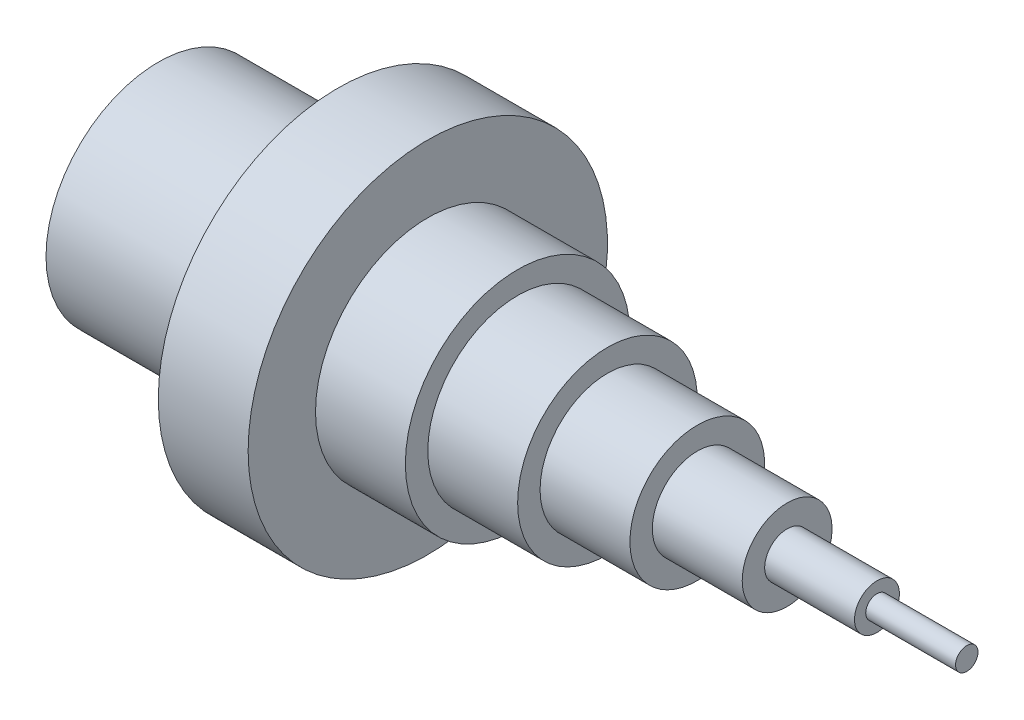
SolidWorks part; units mm, degrees
ref_plane "Alzado" through (0, 0, 0) normal (0, 0, 1) x (1, 0, 0)
ref_plane "Planta" through (0, 0, 0) normal (0, 1, 0) x (1, 0, 0)
ref_plane "Vista lateral" through (0, 0, 0) normal (1, 0, 0) x (0, 0, -1)
sketch "Croquis1" plane through (0, 0, 0) normal (0, 0, 1) x (1, 0, 0)
  line L0 (0, 0) -> (0, 25)
  line L1 (0, 25) -> (40, 25)
  line L2 (40, 25) -> (40, 40)
  line L3 (40, 40) -> (60, 40)
  line L4 (60, 40) -> (60, 25)
  line L5 (60, 25) -> (80, 25)
  line L6 (80, 25) -> (80, 20)
  line L7 (80, 20) -> (100, 20)
  line L8 (100, 20) -> (100, 15)
  line L9 (100, 15) -> (120, 15)
  line L10 (120, 15) -> (120, 10)
  line L11 (120, 10) -> (140, 10)
  line L12 (140, 10) -> (140, 5)
  line L13 (140, 5) -> (160, 5)
  line L16 (160, 5) -> (160, 2.5)
  line L17 (160, 2.5) -> (180, 2.5)
  line L18 (180, 2.5) -> (180, 0)
  line L20 (0, 0) -> (180, 0)
  point P17 (0, 0)
  point P19 (0, 0)
  point P21 (40.6268, 16.3533)
  dimension "D1" = 2.5
  dimension "D2" = 5
  dimension "D3" = 10
  dimension "D4" = 15
  dimension "D5" = 20
  dimension "D6" = 25
  dimension "D7" = 40
  dimension "D8" = 20
  dimension "D9" = 20
  dimension "D10" = 20
  dimension "D11" = 20
  dimension "D12" = 20
  dimension "D13" = 20
  dimension "D15" = 180
  dimension "D14" = 40
revolve "Revolución1" add sketch "Croquis1" angle 360 about L20
sketch "Croquis2" plane through (0, 0, 0) normal (-1, 0, 0) x (0, 0, 1)
  circle A0 centre (0, 0) radius 20
  dimension "D1" = 40
extrude "Cortar-Extruir1" cut sketch "Croquis2" against normal blind 40
equation "\"A\"= 10"
equation "\"B\"= 5"
equation "\"D1@Croquis1\"=\"B\"/2"
equation "\"D2@Croquis1\"=\"A\"/2"
equation "\"D3@Croquis1\"=\"D2@Croquis1\"*2"
equation "\"D4@Croquis1\"=\"D2@Croquis1\"*3"
equation "\"D5@Croquis1\"=\"D3@Croquis1\"*2"
equation "\"D6@Croquis1\"=\"D5@Croquis1\"+5"
equation "\"D7@Croquis1\"=\"D5@Croquis1\"*2"
equation "\"D8@Croquis1\"=\"D5@Croquis1\""
equation "\"D9@Croquis1\"=\"D8@Croquis1\""
equation "\"D10@Croquis1\"=\"D8@Croquis1\""
equation "\"D11@Croquis1\"=\"D10@Croquis1\""
equation "\"D12@Croquis1\"=\"D10@Croquis1\""
equation "\"D13@Croquis1\"=\"D9@Croquis1\""
equation "\"D15@Croquis1\"=(\"D7@Croquis1\"+\"D7@Croquis1\"+\"A\")*2"
equation "\"D14@Croquis1\"=\"D7@Croquis1\""
equation "\"D1@Croquis2\"=\"A\"*4"
equation "\"D1@Cortar-Extruir1\"=\"A\"*4"
